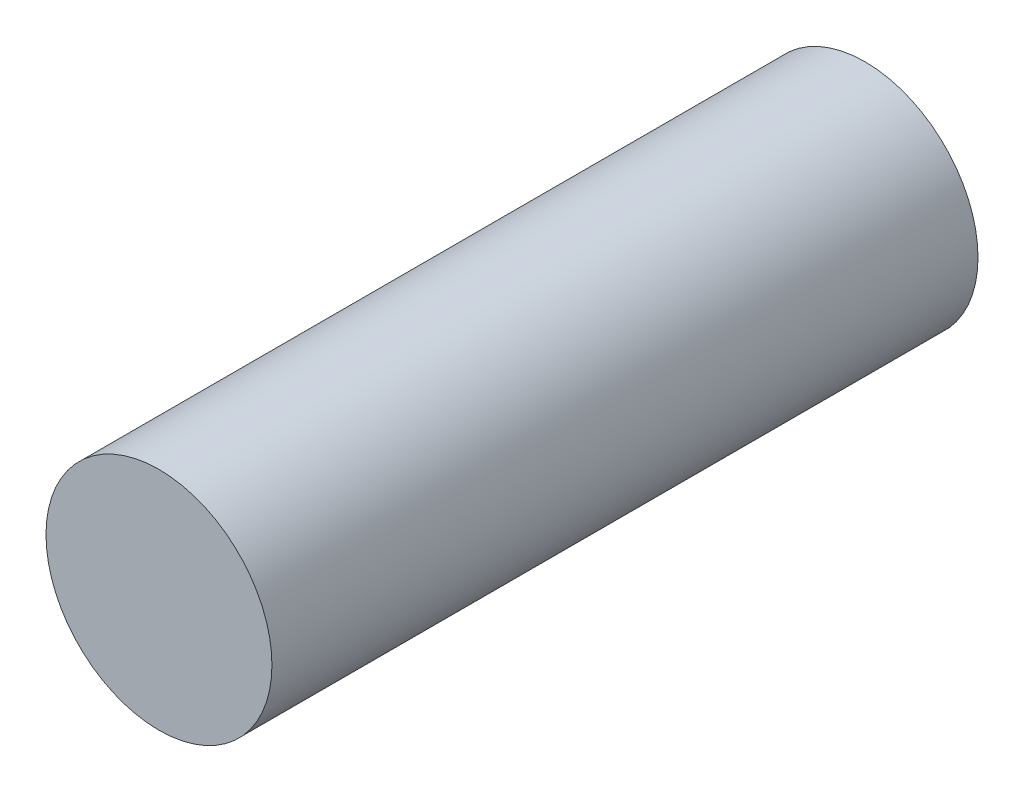
SolidWorks part; units mm, degrees
ref_plane "Alzado" through (0, 0, 0) normal (0, 0, 1) x (1, 0, 0)
ref_plane "Planta" through (0, 0, 0) normal (0, 1, 0) x (1, 0, 0)
ref_plane "Vista lateral" through (0, 0, 0) normal (1, 0, 0) x (0, 0, -1)
sketch "Croquis1" plane through (0, 0, 0) normal (0, 0, 1) x (1, 0, 0)
  circle A0 centre (0, 0) radius 4
  dimension "D1" = 8
extrude "Saliente-Extruir1" add sketch "Croquis1" along normal blind 25
